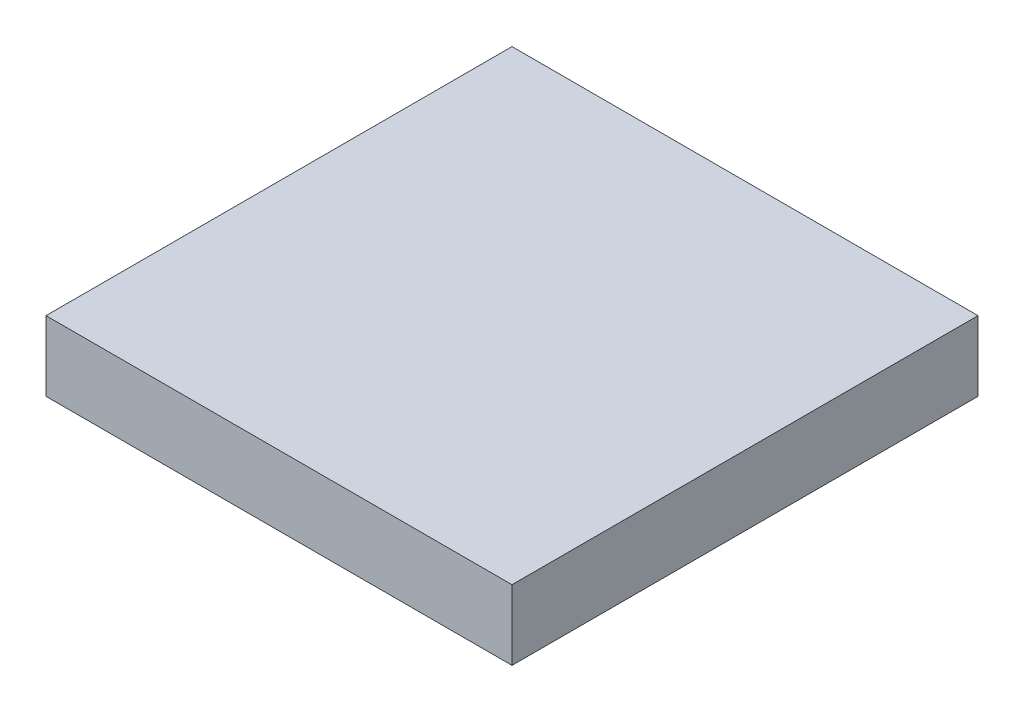
SolidWorks part; units mm, degrees
ref_plane "Front Plane" through (0, 0, 0) normal (0, 0, 1) x (1, 0, 0)
ref_plane "Top Plane" through (0, 0, 0) normal (0, 1, 0) x (1, 0, 0)
ref_plane "Right Plane" through (0, 0, 0) normal (1, 0, 0) x (0, 0, -1)
sketch "Sketch1" plane through (0, 0, 0) normal (0, 1, 0) x (1, 0, 0)
  line L1 (-35.716, -27.5672) -> (65.884, -27.5672)
  line L2 (-35.716, -27.5672) -> (-35.716, 74.0328)
  line L3 (-35.716, 74.0328) -> (65.884, 74.0328)
  line L4 (65.884, -27.5672) -> (65.884, 74.0328)
  dimension "D1" = 101.6
  dimension "D2" = 101.6
extrude "Boss-Extrude1" add sketch "Sketch1" along normal blind 15.24
sketch "Sketch2" plane through (0, 0, 0) normal (0, -1, 0) x (1, 0, 0)
  line L0 (-35.716, 27.5672) -> (65.884, -74.0328) construction
  line L1 (65.884, 27.5672) -> (-35.716, -74.0328) construction
  circle A0 centre (15.084, -23.2328) radius 2.413
  dimension "D1" = 4.826
extrude "Cut-Extrude1" cut sketch "Sketch2" against normal blind 10.16 contours A0
